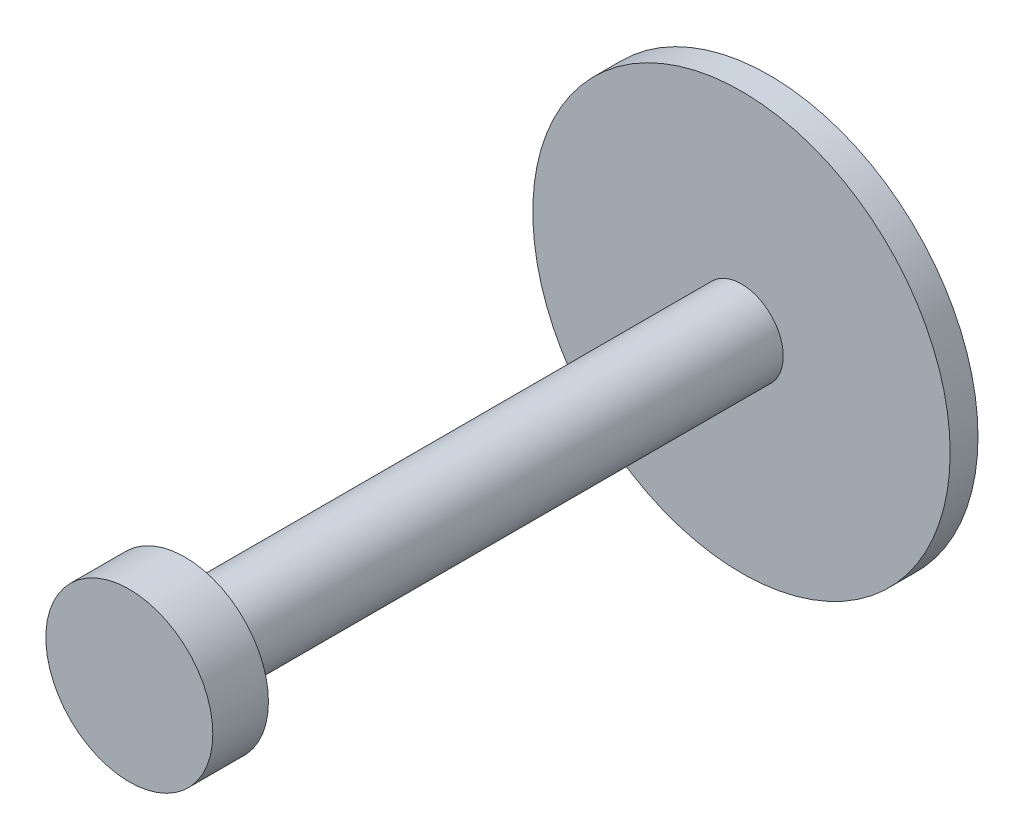
SolidWorks part; units mm, degrees
ref_plane "Front Plane" through (0, 0, 0) normal (0, 0, 1) x (1, 0, 0)
ref_plane "Top Plane" through (0, 0, 0) normal (0, 1, 0) x (1, 0, 0)
ref_plane "Right Plane" through (0, 0, 0) normal (1, 0, 0) x (0, 0, -1)
sketch "Sketch1" plane through (0, 0, 0) normal (0, 0, 1) x (1, 0, 0)
  circle A0 centre (0, 0) radius 75
  dimension "D1" = 150
extrude "Boss-Extrude1" add sketch "Sketch1" along normal blind 10
sketch "Sketch2" plane through (0, 0, 10) normal (0, 0, 1) x (1, 0, 0)
  circle A0 centre (0, 0) radius 15
  dimension "D1" = 30
extrude "Boss-Extrude2" add sketch "Sketch2" along normal blind 200
sketch "Sketch3" plane through (0, 0, 210) normal (0, 0, 1) x (1, 0, 0)
  circle A0 centre (0, 0) radius 30
  dimension "D1" = 60
extrude "Boss-Extrude3" add sketch "Sketch3" along normal blind 20
